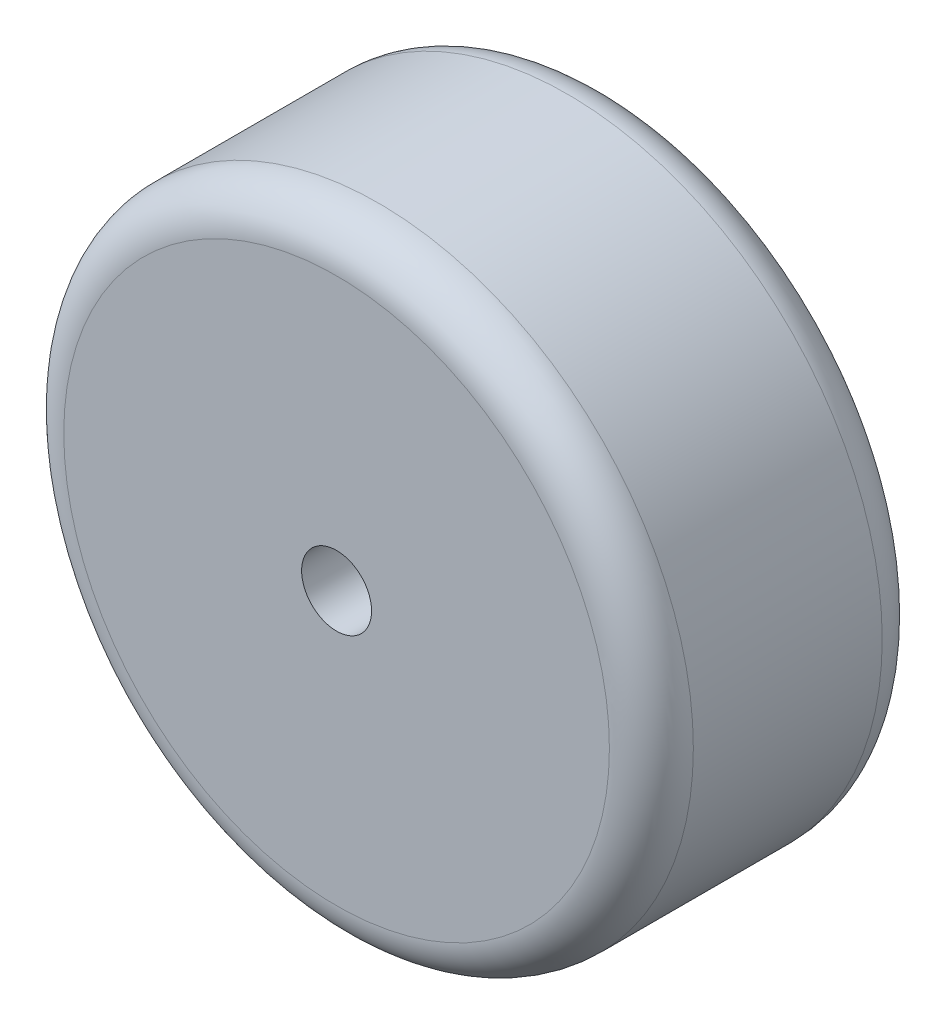
SolidWorks part; units mm, degrees
ref_plane "Front Plane" through (0, 0, 0) normal (0, 0, 1) x (1, 0, 0)
ref_plane "Top Plane" through (0, 0, 0) normal (0, 1, 0) x (1, 0, 0)
ref_plane "Right Plane" through (0, 0, 0) normal (1, 0, 0) x (0, 0, -1)
sketch "Sketch1" plane through (0, 0, 0) normal (0, 0, 1) x (1, 0, 0)
  circle A0 centre (0, 0) radius 38.1
  dimension "D1" = 76.2
extrude "Boss-Extrude1" add sketch "Sketch1" along normal blind 33.02 contours A0
fillet "Fillet1" radius 5.08 2 edges at (38.1, 0, 0) (38.1, 0, 33.02)
scale "Scale1" bodies to scale 101 scale about origin uniform scaling yes scale factor 0.45
sketch "Sketch3" plane through (0, 0, 14.859) normal (0, 0, 1) x (1, 0, 0)
  circle A0 centre (0, 0) radius 1.905
  dimension "D1" = 3.81
extrude "Cut-Extrude1" cut sketch "Sketch3" against normal through all
